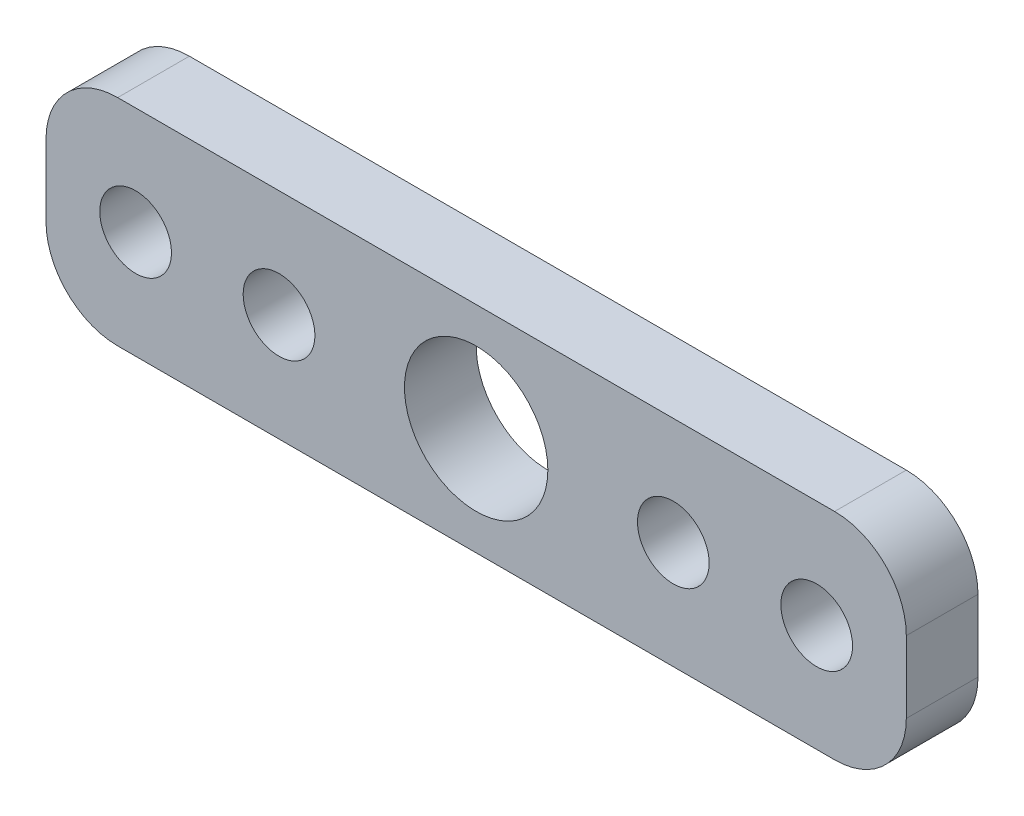
SolidWorks part; units mm, degrees
ref_plane "Front Plane" through (0, 0, 0) normal (0, 0, 1) x (1, 0, 0)
ref_plane "Top Plane" through (0, 0, 0) normal (0, 1, 0) x (1, 0, 0)
ref_plane "Right Plane" through (0, 0, 0) normal (1, 0, 0) x (0, 0, -1)
sketch "Sketch1" plane through (0, 0, 0) normal (0, 0, 1) x (1, 0, 0)
  line L0 (-6.75, 414.8346) -> (17.25, 414.8346) construction
  line L1 (-4.75, 417.8346) -> (15.25, 417.8346)
  line L2 (-6.75, 415.8346) -> (-6.75, 413.8346)
  line L3 (-4.75, 411.8346) -> (15.25, 411.8346)
  line L4 (17.25, 415.8346) -> (17.25, 413.8346)
  line L7 (5.25, 417.8346) -> (5.25, 411.8346) construction
  arc A1 (15.25, 417.8346) -> (17.25, 415.8346) centre (15.25, 415.8346) cw
  arc A2 (15.25, 411.8346) -> (17.25, 413.8346) centre (15.25, 413.8346) ccw
  arc A3 (-6.75, 413.8346) -> (-4.75, 411.8346) centre (-4.75, 413.8346) ccw
  arc A4 (-4.75, 417.8346) -> (-6.75, 415.8346) centre (-4.75, 415.8346) ccw
  circle A5 centre (5.25, 414.8346) radius 2
  circle A6 centre (10.75, 414.8346) radius 1
  circle A7 centre (14.75, 414.8346) radius 1
  circle A8 centre (-0.25, 414.8346) radius 1
  circle A9 centre (-4.25, 414.8346) radius 1
  point P8 (17.25, 417.8346)
  point P11 (17.25, 411.8346)
  point P16 (-6.75, 417.8346)
extrude "Boss-Extrude1" add sketch "Sketch1" along normal blind 2
